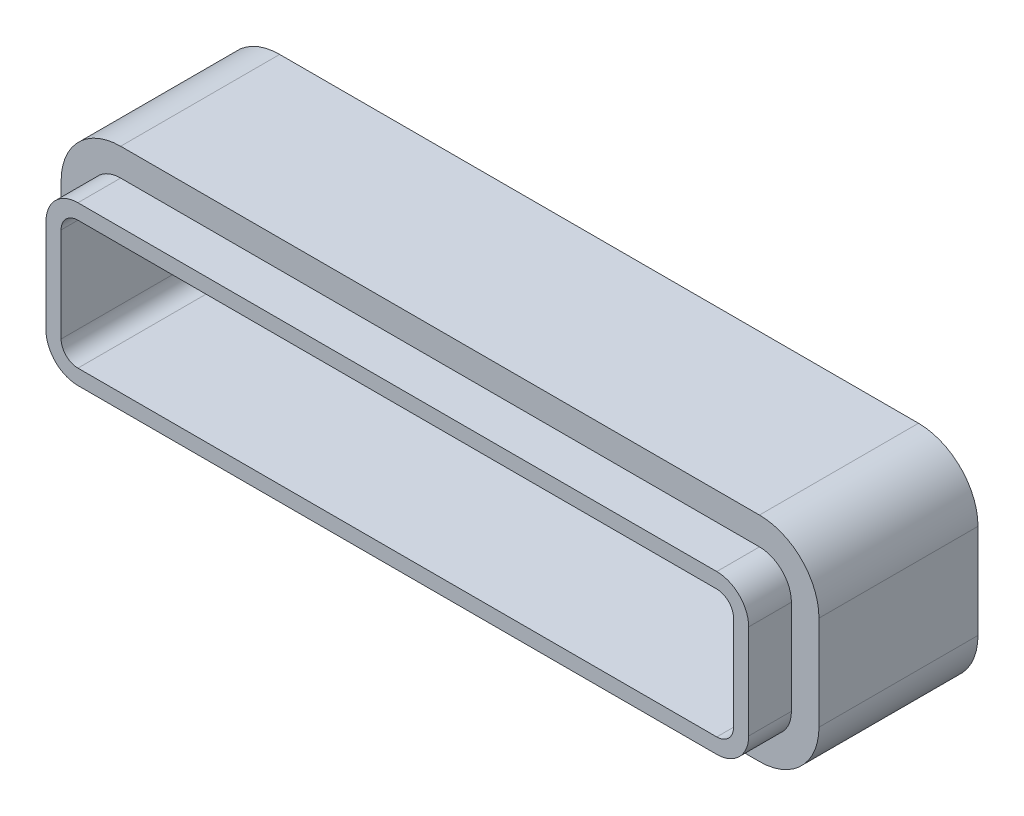
SolidWorks part; units mm, degrees
ref_plane "Plan de face" through (0, 0, 0) normal (0, 0, 1) x (1, 0, 0)
ref_plane "Plan de dessus" through (0, 0, 0) normal (0, 1, 0) x (1, 0, 0)
ref_plane "Plan de droite" through (0, 0, 0) normal (1, 0, 0) x (0, 0, -1)
sketch "Esquisse1" plane through (0, 0, 0) normal (0, 0, 1) x (1, 0, 0)
  line L1 (-95, -31.75) -> (95, -31.75)
  line L2 (-112.7, -14.05) -> (-112.7, 14.05)
  line L3 (-95, 31.75) -> (95, 31.75)
  line L4 (112.7, -14.05) -> (112.7, 14.05)
  line L5 (-112.7, -31.75) -> (112.7, 31.75) construction
  line L6 (-112.7, 31.75) -> (112.7, -31.75) construction
  line L7 (-95, -19.05) -> (95, -19.05)
  line L8 (-100, -14.05) -> (-100, 14.05)
  line L9 (-95, 19.05) -> (95, 19.05)
  line L10 (100, -14.05) -> (100, 14.05)
  line L11 (-100, -19.05) -> (100, 19.05) construction
  line L12 (-100, 19.05) -> (100, -19.05) construction
  arc A0 (95, 31.75) -> (112.7, 14.05) centre (95, 14.05) cw
  arc A1 (95, -31.75) -> (112.7, -14.05) centre (95, -14.05) ccw
  arc A2 (-95, -31.75) -> (-112.7, -14.05) centre (-95, -14.05) cw
  arc A3 (-112.7, 14.05) -> (-95, 31.75) centre (-95, 14.05) cw
  arc A4 (95, 19.05) -> (100, 14.05) centre (95, 14.05) cw
  arc A5 (95, -19.05) -> (100, -14.05) centre (95, -14.05) ccw
  arc A6 (-95, -19.05) -> (-100, -14.05) centre (-95, -14.05) cw
  arc A7 (-100, 14.05) -> (-95, 19.05) centre (-95, 14.05) cw
  point P0 (0, 0)
  point P18 (0, 0)
  dimension "D3" = 17.7
  dimension "D6" = 5
  dimension "D1" = 225.4
  dimension "D2" = 63.5
  dimension "D4" = 200
  dimension "D5" = 38.1
extrude "Boss.-Extru.1" add sketch "Esquisse1" along normal blind 47.3
sketch "Esquisse2" plane through (0, 0, 47.3) normal (0, 0, 1) x (1, 0, 0)
  line L0 (-104.5, 14.05) -> (-104.5, -14.05)
  line L1 (-95, -23.55) -> (95, -23.55)
  line L2 (104.5, -14.05) -> (104.5, 14.05)
  line L3 (95, 23.55) -> (-95, 23.55)
  line L4 (100, -14.05) -> (100, 14.05)
  line L5 (-95, -19.05) -> (95, -19.05)
  line L6 (-100, 14.05) -> (-100, -14.05)
  line L7 (95, 19.05) -> (-95, 19.05)
  line L8 (100, -14.05) -> (100, 14.05)
  line L9 (-95, -19.05) -> (95, -19.05)
  line L10 (-100, 14.05) -> (-100, -14.05)
  line L11 (95, 19.05) -> (-95, 19.05)
  arc A0 (-104.5, -14.05) -> (-95, -23.55) centre (-95, -14.05) ccw
  arc A1 (95, -23.55) -> (104.5, -14.05) centre (95, -14.05) ccw
  arc A2 (104.5, 14.05) -> (95, 23.55) centre (95, 14.05) ccw
  arc A3 (-95, 23.55) -> (-104.5, 14.05) centre (-95, 14.05) ccw
  arc A4 (100, 14.05) -> (95, 19.05) centre (95, 14.05) ccw
  arc A5 (95, -19.05) -> (100, -14.05) centre (95, -14.05) ccw
  arc A6 (-100, -14.05) -> (-95, -19.05) centre (-95, -14.05) ccw
  arc A7 (-95, 19.05) -> (-100, 14.05) centre (-95, 14.05) ccw
  arc A8 (100, 14.05) -> (95, 19.05) centre (95, 14.05) ccw
  arc A9 (95, -19.05) -> (100, -14.05) centre (95, -14.05) ccw
  arc A10 (-100, -14.05) -> (-95, -19.05) centre (-95, -14.05) ccw
  arc A11 (-95, 19.05) -> (-100, 14.05) centre (-95, 14.05) ccw
  dimension "D1" = 0
  dimension "D2" = 4.5
extrude "Boss.-Extru.2" add sketch "Esquisse2" along normal blind 12.7
